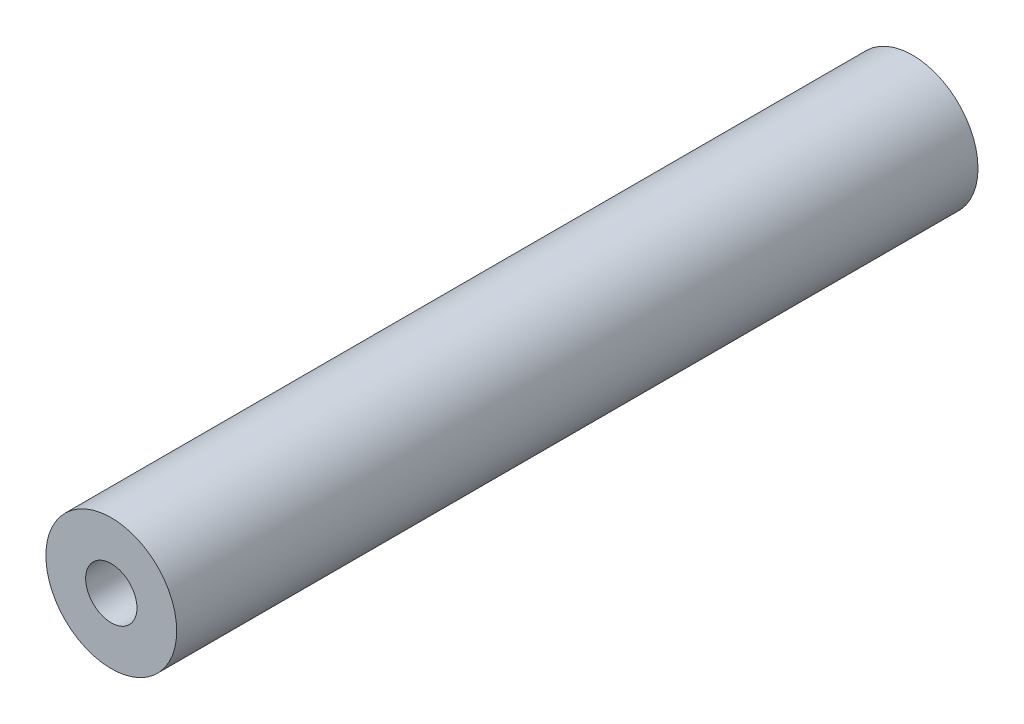
SolidWorks part; units mm, degrees
ref_plane "Front Plane" through (0, 0, 0) normal (0, 0, 1) x (1, 0, 0)
ref_plane "Top Plane" through (0, 0, 0) normal (0, 1, 0) x (1, 0, 0)
ref_plane "Right Plane" through (0, 0, 0) normal (1, 0, 0) x (0, 0, -1)
sketch "Sketch1" plane through (0, 0, 0) normal (0, 0, 1) x (1, 0, 0)
  circle A0 centre (0, 0) radius 6.35
  circle A1 centre (0, 0) radius 2.4892
  dimension "D1" = 4.9784
  dimension "D2" = 12.7
extrude "Boss-Extrude1" add sketch "Sketch1" along normal blind 77.7875
